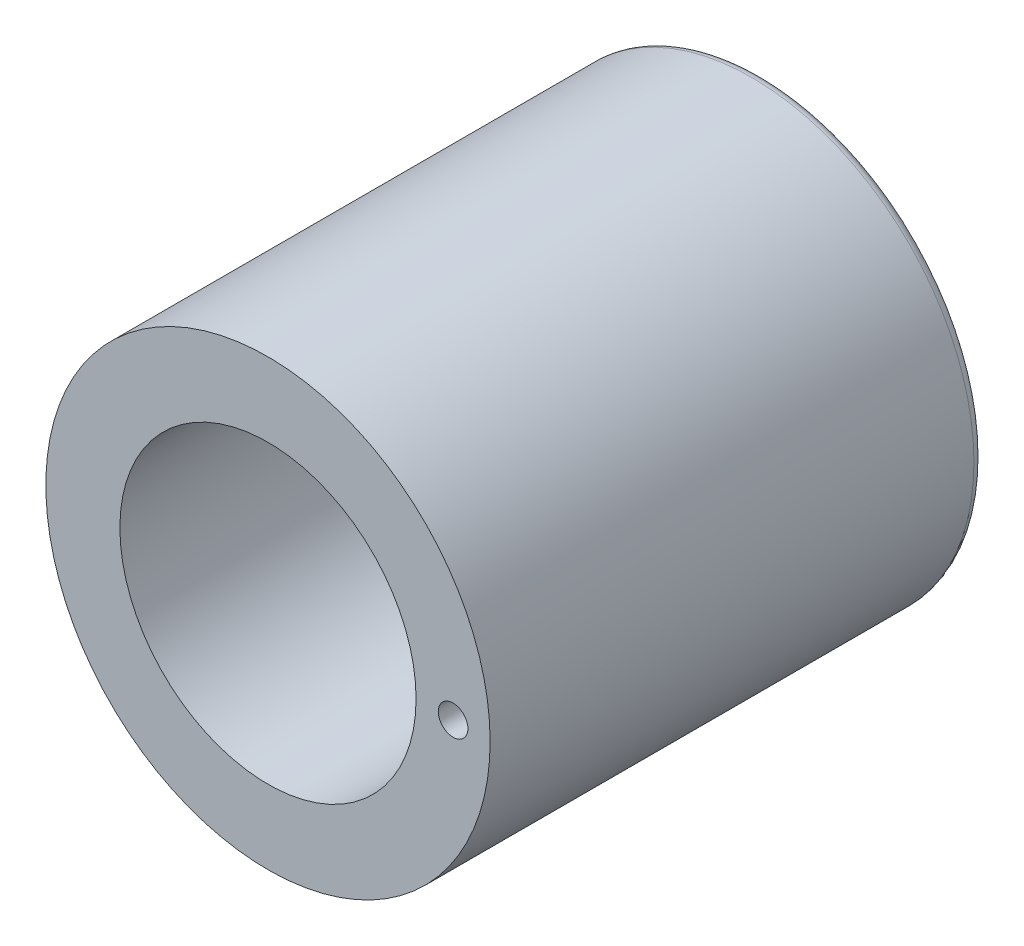
SolidWorks part; units mm, degrees
material "1023 Tôle d'acier au carbone (SS)"
ref_plane "Plan1" through (0, 0, 0) normal (0, 0, 1) x (1, 0, 0)
ref_plane "Plan2" through (0, 0, 0) normal (0, 1, 0) x (1, 0, 0)
ref_plane "Plan3" through (0, 0, 0) normal (1, 0, 0) x (0, 0, -1)
sketch "Esquisse1" plane through (0, 0, 0) normal (0, 0, 1) x (1, 0, 0)
  circle A0 centre (0, 0) radius 45
extrude "Base-Extrusion" add sketch "Esquisse1" along normal blind 100
sketch "Esquisse2" plane through (0, 0, 100) normal (0, 0, 1) x (1, 0, 0)
  circle A0 centre (0, 0) radius 30
extrude "Enlèv. mat.-Extru.1" cut sketch "Esquisse2" against normal blind 100
sketch "Esquisse3" plane through (0, 0, 100) normal (0, 0, 1) x (1, 0, 0)
  circle A0 centre (37.5, 0) radius 3
extrude "Enlèv. mat.-Extru.2" cut sketch "Esquisse3" against normal blind 30
fillet "Congé1" radius 2
ref_plane "Plan4" through (0, 0, 51) normal (0, 0, -1) x (-1, 0, 0)
sketch "G1" plane through (0, 0, 51) normal (0, 0, -1) x (-1, 0, 0)
  point P0 (0, 0)
